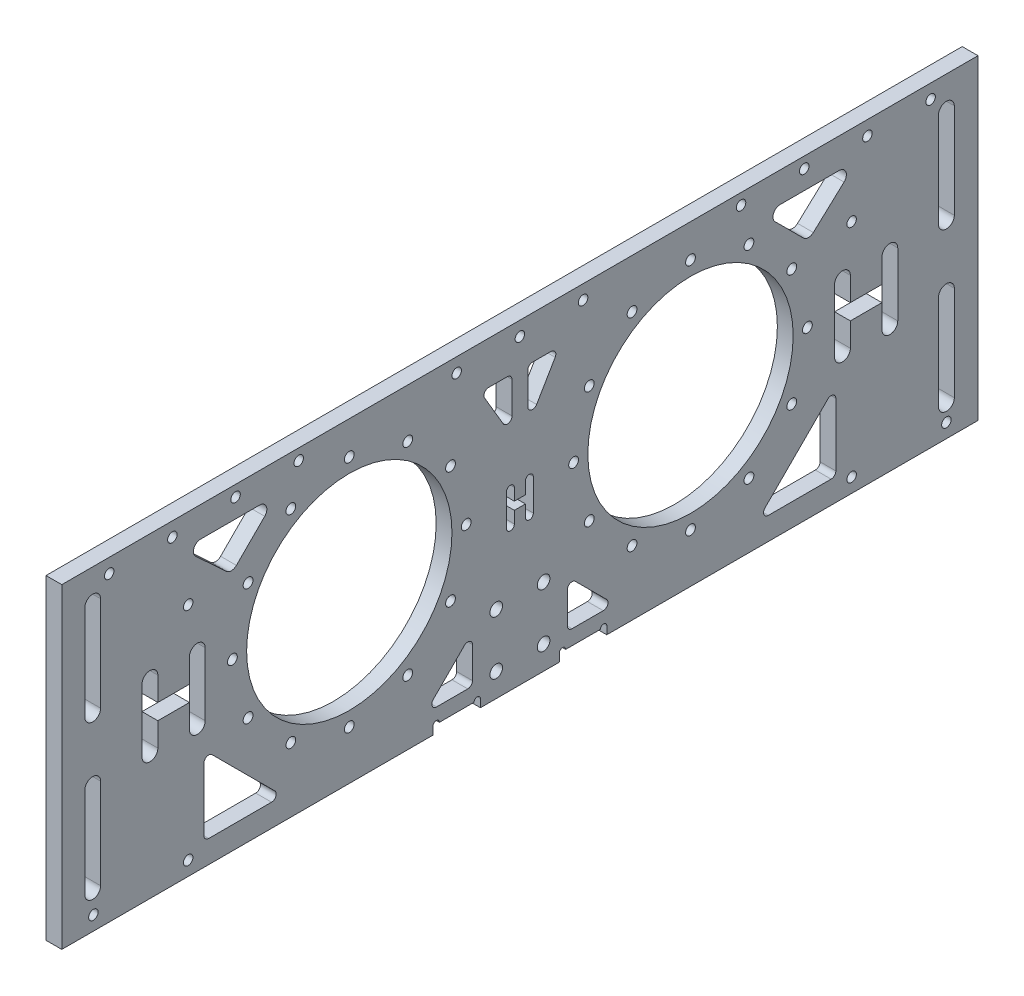
SolidWorks part; units mm, degrees
material "6061 合金"
ref_plane "前视基准面" through (0, 0, 0) normal (0, 0, 1) x (1, 0, 0)
ref_plane "上视基准面" through (0, 0, 0) normal (0, 1, 0) x (1, 0, 0)
ref_plane "右视基准面" through (0, 0, 0) normal (1, 0, 0) x (0, 0, -1)
sketch "草图1" plane through (0, 0, 0) normal (1, 0, 0) x (0, 0, -1)
  line L0 (54, 48) -> (54, -53) construction
  line L1 (-90, -53) -> (198, -53)
  line L2 (-90, -53) -> (-90, 48)
  line L3 (-90, 48) -> (198, 48)
  line L4 (198, -53) -> (198, 48)
  line L5 (-36, 44) -> (-16, 44) construction
  line L6 (46.5, -45) -> (61.5, -45) construction
  line L7 (46.5, -45) -> (46.5, -28) construction
  line L8 (46.5, -28) -> (61.5, -28) construction
  line L9 (61.5, -45) -> (61.5, -28) construction
  line L10 (46.5, -45) -> (61.5, -28) construction
  line L11 (46.5, -28) -> (61.5, -45) construction
  line L12 (144, 44) -> (124, 44) construction
  circle A0 centre (0, 0) radius 32.5
  circle A1 centre (0, 0) radius 37 construction
  circle A2 centre (0, 37) radius 1.55
  circle A3 centre (18.5, 32.0429) radius 1.55
  circle A4 centre (32.0429, 18.5) radius 1.55
  circle A5 centre (37, 0) radius 1.55
  circle A6 centre (32.0429, -18.5) radius 1.55
  circle A7 centre (18.5, -32.0429) radius 1.55
  circle A8 centre (0, -37) radius 1.55
  circle A9 centre (-18.5, -32.0429) radius 1.55
  circle A10 centre (-32.0429, -18.5) radius 1.55
  circle A11 centre (-37, 0) radius 1.55
  circle A12 centre (-32.0429, 18.5) radius 1.55
  circle A13 centre (-18.5, 32.0429) radius 1.55
  circle A14 centre (126.5, 32.0429) radius 1.55
  circle A15 centre (140.0429, 18.5) radius 1.55
  circle A16 centre (145, 0) radius 1.55
  circle A17 centre (140.0429, -18.5) radius 1.55
  circle A18 centre (126.5, -32.0429) radius 1.55
  circle A19 centre (108, -37) radius 1.55
  circle A20 centre (89.5, -32.0429) radius 1.55
  circle A21 centre (75.9571, -18.5) radius 1.55
  circle A22 centre (71, 0) radius 1.55
  circle A23 centre (75.9571, 18.5) radius 1.55
  circle A24 centre (89.5, 32.0429) radius 1.55
  circle A25 centre (108, 37) radius 1.55
  circle A26 centre (108, 0) radius 37 construction
  circle A27 centre (108, 0) radius 32.5
  circle A28 centre (0, 0) radius 46 construction
  circle A29 centre (108, 0) radius 46 construction
  circle A30 centre (61.5, -28) radius 2
  circle A31 centre (46.5, -28) radius 2
  circle A32 centre (46.5, -45) radius 2
  circle A33 centre (61.5, -45) radius 2
  circle A34 centre (-16, 44) radius 1.5
  circle A35 centre (-36, 44) radius 1.5
  circle A36 centre (124, 44) radius 1.5
  circle A37 centre (144, 44) radius 1.5
  point P63 (54, -36.5)
  dimension "D1" = 65
  dimension "D2" = 74
  dimension "D4" = 3.1
  dimension "D9" = 92
  dimension "D13" = 4
  dimension "D17" = 3
  dimension "D5" = 53
  dimension "D6" = 48
  dimension "D7" = 90
  dimension "D8" = 108
  dimension "D10" = 25
  dimension "D11" = 17
  dimension "D12" = 15
  dimension "D14" = 70
  dimension "D15" = 20
  dimension "D16" = 4
  dimension "D3" = 12
extrude "凸台-拉伸1" add sketch "草图1" along normal blind 5
sketch "草图2" plane through (5, 0, 0) normal (1, 0, 0) x (0, 0, -1)
  line L0 (-76, 43) -> (-56, 43) construction
  line L1 (54, 48) -> (54, -53) construction
  line L2 (198, 48) -> (-90, 48) construction
  line L3 (-90, -53) -> (198, -53) construction
  line L4 (184, 43) -> (164, 43) construction
  line L5 (-90, 48) -> (-90, -53) construction
  line L6 (34, 43) -> (54, 43) construction
  circle A0 centre (-76, 43) radius 1.5
  circle A1 centre (-56, 43) radius 1.5
  circle A2 centre (164, 43) radius 1.5
  circle A3 centre (184, 43) radius 1.5
  circle A4 centre (34, 43) radius 1.5
  circle A5 centre (54, 43) radius 1.5
  circle A6 centre (74, 43) radius 1.5
  dimension "D1" = 14
  dimension "D4" = 3
  dimension "D6" = 3
  dimension "D2" = 20
  dimension "D3" = 5
  dimension "D5" = 20
extrude "切除-拉伸1" cut sketch "草图2" against normal through all
sketch "草图3" plane through (5, 0, 0) normal (1, 0, 0) x (0, 0, -1)
  line L0 (-81, -48) -> (-51, -48) construction
  line L1 (-90, 48) -> (-90, -53) construction
  line L2 (-90, -53) -> (198, -53) construction
  line L3 (54, 48) -> (54, -53) construction
  line L4 (198, 48) -> (-90, 48) construction
  line L5 (-81, -48) -> (-81, 22) construction
  line L6 (-81, 22) -> (-51, 22) construction
  line L7 (-51, 22) -> (-51, -48) construction
  line L8 (159, 22) -> (159, -48) construction
  line L9 (189, 22) -> (159, 22) construction
  line L10 (189, -48) -> (189, 22) construction
  line L11 (189, -48) -> (159, -48) construction
  circle A0 centre (-81, -48) radius 1.5
  circle A1 centre (-51, -48) radius 1.5
  circle A2 centre (-81, 22) radius 1.5
  circle A3 centre (-51, 22) radius 1.5
  circle A4 centre (159, 22) radius 1.5
  circle A5 centre (189, 22) radius 1.5
  circle A6 centre (159, -48) radius 1.5
  circle A7 centre (189, -48) radius 1.5
  dimension "D3" = 3
  dimension "D1" = 9
  dimension "D2" = 5
  dimension "D4" = 30
  dimension "D5" = 70
extrude "切除-拉伸2" cut sketch "草图3" against normal blind 10
sketch "草图4" plane through (5, 0, 0) normal (1, 0, 0) x (0, 0, -1)
  line L0 (44.1226, 34) -> (50, 34)
  line L1 (51.5, 32.5) -> (51.5, 22.5085)
  line L2 (48.7071, 21.7479) -> (42.8297, 31.7395)
  line L3 (54, 48) -> (54, -53) construction
  line L4 (198, 48) -> (-90, 48) construction
  line L5 (-90, -53) -> (198, -53) construction
  line L6 (56.5, 32.5) -> (56.5, 22.5085)
  line L7 (63.8774, 34) -> (58, 34)
  line L8 (59.2929, 21.7479) -> (65.1703, 31.7395)
  line L10 (-81, 22) -> (-51, 22) construction
  line L11 (-81, 22) -> (-81, -48) construction
  line L12 (-81, -48) -> (-51, -48) construction
  line L13 (-51, 22) -> (-51, -48) construction
  line L19 (-46, -23.949) -> (-46, -43.8277)
  line L20 (-44.5, -45.3277) -> (-24.6213, -45.3277)
  line L21 (-23.5607, -42.767) -> (-43.4393, -22.8883)
  line L25 (-47.0663, 38) -> (-28.3731, 38)
  line L26 (-26.7654, 34.1187) -> (-35.7353, 25.1488)
  line L27 (-38.8847, 25.0853) -> (-48.608, 34.0552)
  line L34 (27.6213, -45.3277) -> (37.5, -45.3277)
  line L35 (39, -43.8277) -> (39, -33.949)
  line L36 (36.4393, -32.8883) -> (26.5607, -42.767)
  line L37 (71.5607, -32.8883) -> (81.4393, -42.767)
  line L38 (69, -43.8277) -> (69, -33.949)
  line L39 (80.3787, -45.3277) -> (70.5, -45.3277)
  line L40 (159, 22) -> (159, -48) construction
  line L41 (189, -48) -> (159, -48) construction
  line L42 (189, 22) -> (189, -48) construction
  line L43 (189, 22) -> (159, 22) construction
  line L50 (146.8847, 25.0853) -> (156.608, 34.0552)
  line L51 (134.7654, 34.1187) -> (143.7353, 25.1488)
  line L52 (155.0663, 38) -> (136.3731, 38)
  line L56 (131.5607, -42.767) -> (151.4393, -22.8883)
  line L57 (152.5, -45.3277) -> (132.6213, -45.3277)
  line L58 (154, -23.949) -> (154, -43.8277)
  arc A0 (51.5, 22.5085) -> (48.7071, 21.7479) centre (50, 22.5085) cw
  arc A1 (50, 34) -> (51.5, 32.5) centre (50, 32.5) cw
  arc A2 (44.1226, 34) -> (42.8297, 31.7395) centre (44.1226, 32.5) ccw
  arc A3 (58, 34) -> (56.5, 32.5) centre (58, 32.5) ccw
  arc A4 (56.5, 22.5085) -> (59.2929, 21.7479) centre (58, 22.5085) ccw
  arc A5 (63.8774, 34) -> (65.1703, 31.7395) centre (63.8774, 32.5) cw
  arc A14 (-24.6213, -45.3277) -> (-23.5607, -42.767) centre (-24.6213, -43.8277) ccw
  arc A15 (-46, -43.8277) -> (-44.5, -45.3277) centre (-44.5, -43.8277) ccw
  arc A16 (-46, -23.949) -> (-43.4393, -22.8883) centre (-44.5, -23.949) cw
  arc A23 (-28.3731, 38) -> (-26.7654, 34.1187) centre (-28.3731, 35.7264) cw
  arc A24 (-35.7353, 25.1488) -> (-38.8847, 25.0853) centre (-37.343, 26.7565) cw
  arc A25 (-47.0663, 38) -> (-48.608, 34.0552) centre (-47.0663, 35.7264) ccw
  arc A29 (27.6213, -45.3277) -> (26.5607, -42.767) centre (27.6213, -43.8277) cw
  arc A30 (37.5, -45.3277) -> (39, -43.8277) centre (37.5, -43.8277) ccw
  arc A31 (39, -33.949) -> (36.4393, -32.8883) centre (37.5, -33.949) ccw
  arc A32 (69, -33.949) -> (71.5607, -32.8883) centre (70.5, -33.949) cw
  arc A33 (70.5, -45.3277) -> (69, -43.8277) centre (70.5, -43.8277) cw
  arc A34 (80.3787, -45.3277) -> (81.4393, -42.767) centre (80.3787, -43.8277) ccw
  arc A38 (155.0663, 38) -> (156.608, 34.0552) centre (155.0663, 35.7264) cw
  arc A39 (143.7353, 25.1488) -> (146.8847, 25.0853) centre (145.343, 26.7565) ccw
  arc A40 (136.3731, 38) -> (134.7654, 34.1187) centre (136.3731, 35.7264) ccw
  arc A47 (154, -23.949) -> (151.4393, -22.8883) centre (152.5, -23.949) ccw
  arc A48 (154, -43.8277) -> (152.5, -45.3277) centre (152.5, -43.8277) cw
  arc A49 (132.6213, -45.3277) -> (131.5607, -42.767) centre (132.6213, -43.8277) cw
  point P11 (51.5, 17)
  point P14 (51.5, 34)
  point P17 (41.5, 34)
  point P73 (-21, -45.3277)
  point P76 (-46, -45.3277)
  point P79 (-46, -20.3277)
  point P97 (-22.8841, 38)
  point P102 (-52.8841, 38)
  point P105 (-52, 26)
  point P108 (-77, 26)
  point P111 (-77, 38)
  point P115 (24, -45.3277)
  point P118 (39, -45.3277)
  point P130 (69, -45.3277)
  point P131 (84, -45.3277)
  point P199 (185, 38)
  point P200 (185, 26)
  point P201 (160, 26)
  point P202 (160.8841, 38)
  point P203 (130.8841, 38)
  point P207 (154, -20.3277)
  point P208 (154, -45.3277)
  point P209 (129, -45.3277)
  dimension "D5" = 1.5
  dimension "D26" = 1.5
  dimension "D30" = 1.5
  dimension "D1" = 2.5
  dimension "D2" = 14
  dimension "D3" = 10
  dimension "D4" = 17
  dimension "D14" = 5
  dimension "D15" = 25
  dimension "D16" = 25
  dimension "D17" = 10
  dimension "D19" = 25
  dimension "D21" = 45
  dimension "D22" = 30
  dimension "D27" = 15
  dimension "D28" = 45
  dimension "D29" = 15
extrude "切除-拉伸3" cut sketch "草图4" against normal through all
sketch "草图6" plane through (5, 0, 0) normal (1, 0, 0) x (0, 0, -1)
  line L0 (41.5, -53) -> (41.5, -50)
  line L1 (-90, -53) -> (198, -53) construction
  line L5 (54, 48) -> (54, -53) construction
  line L6 (198, 48) -> (-90, 48) construction
  line L7 (39.5, -50) -> (28.5, -50)
  line L8 (26.5, -50) -> (26.5, -53)
  line L9 (26.5, -53) -> (41.5, -53)
  line L13 (81.5, -53) -> (66.5, -53)
  line L14 (81.5, -50) -> (81.5, -53)
  line L15 (68.5, -50) -> (79.5, -50)
  line L16 (66.5, -53) -> (66.5, -50)
  arc A0 (26.5, -50) -> (28.5, -50) centre (27.5, -50) cw
  arc A1 (41.5, -50) -> (39.5, -50) centre (40.5, -50) ccw
  arc A2 (66.5, -50) -> (68.5, -50) centre (67.5, -50) cw
  arc A3 (81.5, -50) -> (79.5, -50) centre (80.5, -50) ccw
  dimension "D4" = 1
  dimension "D1" = 25
  dimension "D2" = 3
  dimension "D3" = 15
extrude "切除-拉伸4" cut sketch "草图6" against normal through all
sketch "草图8" plane through (5, 0, 0) normal (1, 0, 0) x (0, 0, -1)
  line L0 (-90, -53) -> (-91, -53)
  line L1 (-91, -53) -> (-91, 48)
  line L2 (-91, 48) -> (-90, 48)
  line L3 (-90, 48) -> (-90, -53)
  line L4 (198, -53) -> (199, -53)
  line L5 (199, -53) -> (199, 48)
  line L6 (199, 48) -> (198, 48)
  line L7 (198, 48) -> (198, -53)
extrude "凸台-拉伸3" add sketch "草图8" against normal up to surface (5 mm away) up to face at (0, -38.625, -54)
sketch "草图9" plane through (5, 0, 0) normal (1, 0, 0) x (0, 0, -1)
  line L0 (-91, 48) -> (-91, 47.5)
  line L1 (-91, 48) -> (-91, -53) construction
  line L2 (-91, 47.5) -> (199, 47.5)
  line L3 (199, -53) -> (199, 48) construction
  line L4 (199, 47.5) -> (199, 48)
  line L5 (199, 48) -> (-91, 48)
  line L6 (-91, -53) -> (-91, -52.5)
  line L7 (-91, -52.5) -> (199, -52.5)
  line L8 (199, -52.5) -> (199, -53)
  line L9 (199, -53) -> (-91, -53)
extrude "切除-拉伸5" cut sketch "草图9" against normal blind 10
sketch "草图10" plane through (0, 0, 0) normal (-1, 0, 0) x (0, 0, 1)
  line L0 (91, -2.5) -> (81.2144, -2.5)
  line L1 (91, 47.5) -> (91, -52.5) construction
  line L2 (81.2144, -2.5) -> (81.2144, 7.5)
  line L3 (81.2144, -2.5) -> (81.2144, -12.5)
  line L4 (81.2144, 7.5) -> (81.2144, 37.5) construction
  line L5 (78.7144, 7.5) -> (78.7144, 37.5)
  line L6 (83.7144, 7.5) -> (83.7144, 37.5)
  line L7 (81.2144, -12.5) -> (81.2144, -41.1754) construction
  line L8 (83.7144, -12.5) -> (83.7144, -41.1754)
  line L9 (78.7144, -12.5) -> (78.7144, -41.1754)
  line L10 (-199, -2.5) -> (-189, -2.5)
  line L11 (-199, -52.5) -> (-199, 47.5) construction
  line L12 (-189, -2.5) -> (-189, 7.5)
  line L13 (-189, -2.5) -> (-189, -12.5)
  line L14 (-189, 7.5) -> (-189, 37.5) construction
  line L15 (-191.5, 7.5) -> (-191.5, 37.5)
  line L16 (-186.5, 7.5) -> (-186.5, 37.5)
  line L17 (-189, -12.5) -> (-189, -42.5) construction
  line L18 (-186.5, -12.5) -> (-186.5, -42.5)
  line L19 (-191.5, -12.5) -> (-191.5, -42.5)
  arc A0 (78.7144, 7.5) -> (83.7144, 7.5) centre (81.2144, 7.5) ccw
  arc A1 (83.7144, 37.5) -> (78.7144, 37.5) centre (81.2144, 37.5) ccw
  arc A2 (83.7144, -12.5) -> (78.7144, -12.5) centre (81.2144, -12.5) ccw
  arc A3 (78.7144, -41.1754) -> (83.7144, -41.1754) centre (81.2144, -41.1754) ccw
  arc A4 (-191.5, 7.5) -> (-186.5, 7.5) centre (-189, 7.5) ccw
  arc A5 (-186.5, 37.5) -> (-191.5, 37.5) centre (-189, 37.5) ccw
  arc A6 (-186.5, -12.5) -> (-191.5, -12.5) centre (-189, -12.5) ccw
  arc A7 (-191.5, -42.5) -> (-186.5, -42.5) centre (-189, -42.5) ccw
  point P4 (81.2144, 22.5)
  point P12 (81.2144, -26.8377)
  point P24 (-189, 22.5)
  point P30 (-189, -27.5)
  dimension "D1" = 10
  dimension "D2" = 10
  dimension "D3" = 10
  dimension "D4" = 10
  dimension "D5" = 10
extrude "切除-拉伸6" cut sketch "草图10" against normal blind 10
sketch "草图11" plane through (0, 0, 0) normal (-1, 0, 0) x (0, 0, 1)
  line L0 (-199, -2.5) -> (-171.1008, -2.5)
  line L1 (-199, -52.5) -> (-199, 47.5) construction
  line L2 (-171.1008, -2.5) -> (-171.1008, 7.5)
  line L3 (-171.1008, -2.5) -> (-171.1008, -12.5)
  line L4 (-171.1008, -2.5) -> (-156.1008, -2.5)
  line L5 (-156.1008, -2.5) -> (-156.1008, 7.5)
  line L6 (-156.1008, -2.5) -> (-156.1008, -12.5)
  line L7 (-171.1008, 7.5) -> (-171.1008, -12.5) construction
  line L10 (-156.1008, 7.5) -> (-156.1008, -12.5) construction
  line L11 (-153.6008, 7.5) -> (-153.6008, -12.5)
  line L12 (-158.6008, 7.5) -> (-158.6008, -12.5)
  line L13 (-168.6008, 7.5) -> (-168.6008, -12.5)
  line L14 (-173.6008, 7.5) -> (-173.6008, -12.5)
  line L15 (-171.1008, -2.5) -> (-156.1008, -2.5) construction
  line L16 (-171.1008, 0) -> (-156.1008, 0)
  line L17 (-171.1008, -5) -> (-156.1008, -5)
  line L18 (-54, 47.5) -> (-54, -52.5)
  line L19 (-199, 47.5) -> (91, 47.5) construction
  line L20 (-41.5, -52.5) -> (-66.5, -52.5) construction
  line L21 (48.1008, 7.5) -> (48.1008, -12.5) construction
  line L22 (45.6008, 7.5) -> (45.6008, -12.5)
  line L23 (50.6008, 7.5) -> (50.6008, -12.5)
  line L24 (63.1008, 7.5) -> (63.1008, -12.5) construction
  line L25 (60.6008, 7.5) -> (60.6008, -12.5)
  line L26 (65.6008, 7.5) -> (65.6008, -12.5)
  line L27 (63.1008, -2.5) -> (48.1008, -2.5) construction
  line L28 (63.1008, 0) -> (48.1008, 0)
  line L29 (63.1008, -5) -> (48.1008, -5)
  arc A2 (-153.6008, 7.5) -> (-158.6008, 7.5) centre (-156.1008, 7.5) ccw
  arc A3 (-158.6008, -12.5) -> (-153.6008, -12.5) centre (-156.1008, -12.5) ccw
  arc A4 (-168.6008, 7.5) -> (-173.6008, 7.5) centre (-171.1008, 7.5) ccw
  arc A5 (-173.6008, -12.5) -> (-168.6008, -12.5) centre (-171.1008, -12.5) ccw
  arc A6 (-171.1008, 0) -> (-171.1008, -5) centre (-171.1008, -2.5) ccw
  arc A7 (-156.1008, -5) -> (-156.1008, 0) centre (-156.1008, -2.5) ccw
  arc A8 (45.6008, 7.5) -> (50.6008, 7.5) centre (48.1008, 7.5) cw
  arc A9 (50.6008, -12.5) -> (45.6008, -12.5) centre (48.1008, -12.5) cw
  arc A10 (60.6008, 7.5) -> (65.6008, 7.5) centre (63.1008, 7.5) cw
  arc A11 (65.6008, -12.5) -> (60.6008, -12.5) centre (63.1008, -12.5) cw
  arc A12 (63.1008, 0) -> (63.1008, -5) centre (63.1008, -2.5) cw
  arc A13 (48.1008, -5) -> (48.1008, 0) centre (48.1008, -2.5) cw
  point P4 (-171.1008, -2.5)
  point P14 (-156.1008, -2.5)
  point P19 (-163.6008, -2.5)
  point P32 (48.1008, -2.5)
  point P39 (63.1008, -2.5)
  point P46 (55.6008, -2.5)
  dimension "D1" = 15
extrude "切除-拉伸7" cut sketch "草图11" against normal blind 10
sketch "草图12" plane through (5, 0, 0) normal (1, 0, 0) x (0, 0, -1)
  line L0 (54, 47.5) -> (54, -52.5)
  line L1 (54, -2.5) -> (52.25, -2.5)
  line L2 (51, -1.25) -> (51, 2.5)
  line L3 (-91, 47.5) -> (199, 47.5) construction
  line L4 (66.5, -52.5) -> (41.5, -52.5) construction
  line L5 (54, -2.5) -> (57.75, -2.5)
  line L6 (57, -1.25) -> (57, 2.5)
  line L7 (57, -2.5) -> (57, -7.5)
  line L8 (51, -2.5) -> (51, -7.5)
  line L9 (51, 2.5) -> (51, -1.25) construction
  line L10 (52.25, 2.5) -> (52.25, -1.25)
  line L11 (49.75, 2.5) -> (49.75, -7.5)
  line L12 (57, 2.5) -> (57, -1.25) construction
  line L13 (58.25, 2.5) -> (58.25, -7.5)
  line L14 (55.75, 2.5) -> (55.75, -1.25)
  line L15 (52.25, -2.5) -> (57.75, -2.5) construction
  line L16 (52.25, -1.25) -> (55.75, -1.25)
  line L17 (52.25, -3.75) -> (55.75, -3.75)
  line L18 (52.25, -3.75) -> (52.25, -7.5)
  line L19 (51, -2.5) -> (51, -7.5) construction
  line L20 (57, -2.5) -> (57, -7.5) construction
  line L21 (55.75, -3.75) -> (55.75, -7.5)
  arc A0 (52.25, 2.5) -> (49.75, 2.5) centre (51, 2.5) ccw
  arc A1 (49.75, -7.5) -> (52.25, -7.5) centre (51, -7.5) ccw
  arc A2 (58.25, 2.5) -> (55.75, 2.5) centre (57, 2.5) ccw
  arc A3 (55.75, -7.5) -> (58.25, -7.5) centre (57, -7.5) ccw
  point P13 (49, -2.5)
  point P20 (59, -2.5)
  point P25 (54, -2.5)
  dimension "D1" = 3
  dimension "D2" = 5
  dimension "D3" = 5
  dimension "D4" = 5
  dimension "D5" = 5
  dimension "D6" = 3
extrude "切除-拉伸8" cut sketch "草图12" against normal blind 10
